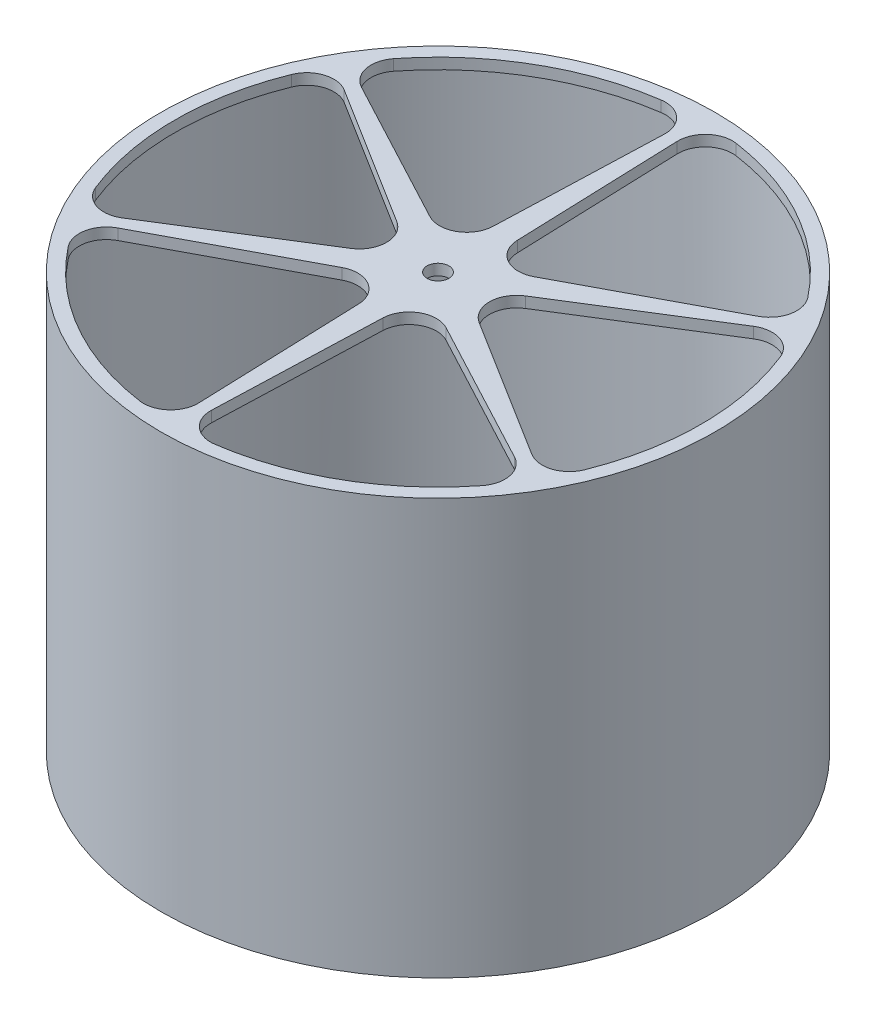
SolidWorks part; units mm, degrees
ref_plane "Front Plane" through (0, 0, 0) normal (0, 0, 1) x (1, 0, 0)
ref_plane "Top Plane" through (0, 0, 0) normal (0, 1, 0) x (1, 0, 0)
ref_plane "Right Plane" through (0, 0, 0) normal (1, 0, 0) x (0, 0, -1)
sketch "Sketch1" plane through (0, 0, 0) normal (0, 1, 0) x (1, 0, 0)
  circle A0 centre (0, 0) radius 101.6
  dimension "D1" = 203.2
extrude "Boss-Extrude1" add sketch "Sketch1" along normal blind 4
sketch "Sketch3" plane through (0, 0, 0) normal (1, 0, 0) x (0, 0, -1)
  line L0 (0, 0) -> (0, 51.7473)
sketch "Sketch2" plane through (0, 0, 0) normal (0, 1, 0) x (1, 0, 0)
  line L0 (0, 0) -> (141.2438, 0) construction
  line L1 (23.5716, 8.4805) -> (75.094, 40.6752)
  line L2 (84.6062, 46.6191) -> (84.6062, -46.6191) construction
  line L6 (75.094, -40.6752) -> (23.5716, -8.4805)
  arc A0 (89.6764, 35.9124) -> (89.6764, -35.9124) centre (0, 0) cw
  circle A1 centre (0, 0) radius 101.6 construction
  arc A4 (23.5716, -8.4805) -> (23.5716, 8.4805) centre (28.8708, 0) cw
  arc A5 (75.094, 40.6752) -> (89.6764, 35.9124) centre (80.3932, 32.1947) cw
  arc A6 (89.6764, -35.9124) -> (75.094, -40.6752) centre (80.3932, -32.1947) cw
  point P7 (84.6062, 0)
  point P11 (10, 0)
  dimension "D1" = 32
  dimension "D2" = 5
  dimension "D3" = 10
  dimension "D4" = 10
  dimension "D5" = 10
extrude "Cut-Extrude2" cut sketch "Sketch2" along normal through all
pattern_circular "CirPattern1" count 6 over 360 about axis through (0, 0, 0) along (0, 1, 0) of "Cut-Extrude2"
sketch "Sketch5" plane through (0, 0, 0) normal (0, 1, 0) x (1, 0, 0)
  circle A0 centre (0, 0) radius 4
  dimension "D1" = 8
extrude "Cut-Extrude3" cut sketch "Sketch5" along normal through all
sketch "Sketch6" plane through (0, 0, 0) normal (0, -1, 0) x (1, 0, 0)
  circle A0 centre (0, 0) radius 101.6
  circle A1 centre (0, 0) radius 100.6
  dimension "D1" = 1
  dimension "D2" = 203.2
extrude "Boss-Extrude2" add sketch "Sketch6" along normal blind 148.4
fillet "Fillet1" radius 2 1 edges at (0, 0, -100.6)
